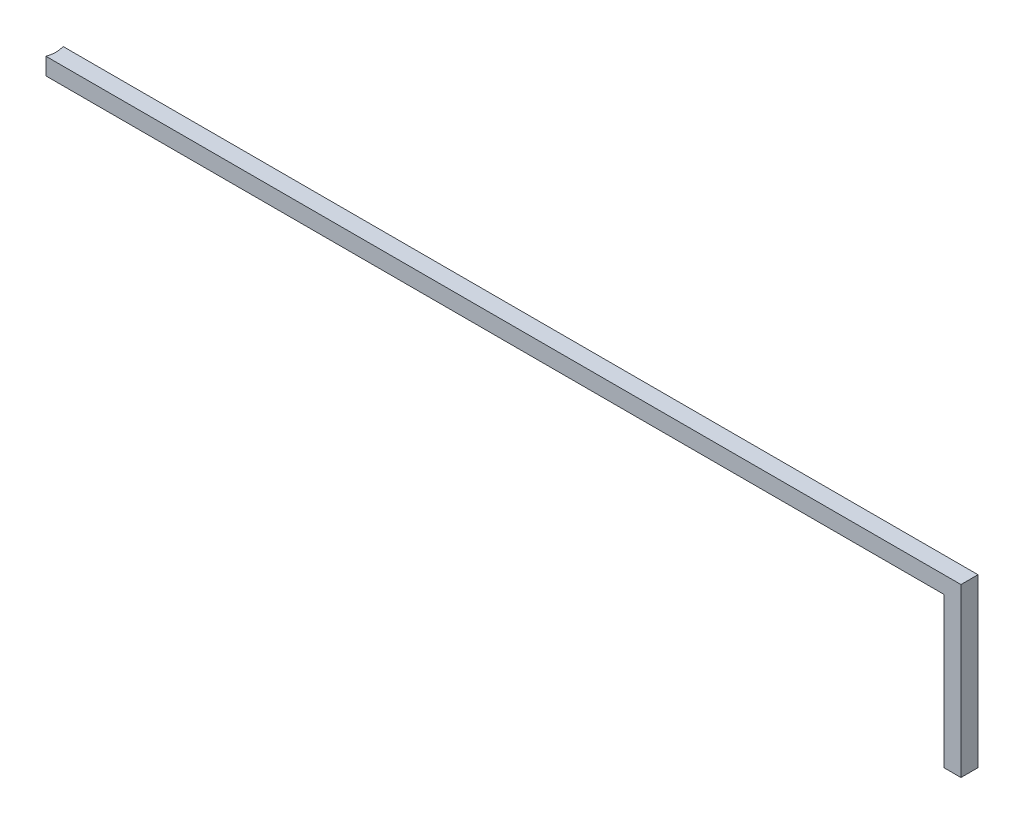
SolidWorks part; units mm, degrees
ref_plane "前视基准面" through (0, 0, 0) normal (0, 0, 1) x (1, 0, 0)
ref_plane "上视基准面" through (0, 0, 0) normal (0, 1, 0) x (1, 0, 0)
ref_plane "右视基准面" through (0, 0, 0) normal (1, 0, 0) x (0, 0, -1)
sketch "草图2" plane through (0, 0, 0) normal (0, 0, 1) x (1, 0, 0)
  line L0 (77.3845, -105.3706) -> (61.8845, -105.3706)
  line L1 (61.8845, -105.3706) -> (61.8845, 31.1294)
  line L2 (61.8845, 31.1294) -> (-757.0345, 31.1294)
  line L3 (-757.0345, 31.1294) -> (-757.0345, 46.6294)
  line L4 (-757.0345, 46.6294) -> (77.3845, 46.6294)
  line L5 (77.3845, 46.6294) -> (77.3845, -105.3706)
  dimension "D1" = 152
  dimension "D2" = 15.5
  dimension "D3" = 15.5
extrude "凸台-拉伸1" add sketch "草图2" along normal blind 15.5
sketch "草图3" plane through (0, 46.6294, 0) normal (0, 1, 0) x (1, 0, 0)
  circle A0 centre (-777.3513, -7.75) radius 24
extrude "切除-拉伸1" cut sketch "草图3" against normal blind 15.5
